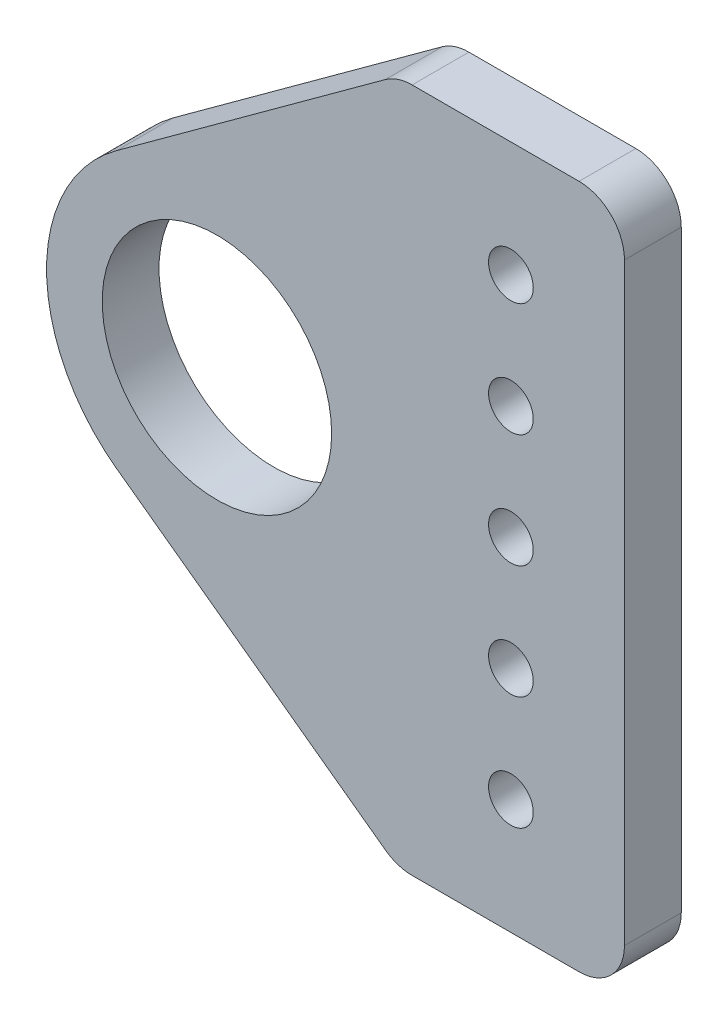
SolidWorks part; units mm, degrees
ref_plane "Front Plane" through (0, 0, 0) normal (0, 0, 1) x (1, 0, 0)
ref_plane "Top Plane" through (0, 0, 0) normal (0, 1, 0) x (1, 0, 0)
ref_plane "Right Plane" through (0, 0, 0) normal (1, 0, 0) x (0, 0, -1)
sketch "Sketch1" plane through (0, 0, 0) normal (0, 0, 1) x (1, 0, 0)
  line L0 (7.62, 952.6788) -> (-11.045, 952.6788)
  line L1 (12.7, 1181.1) -> (12.7, 876.3) construction
  line L2 (-12.7, 1181.1) -> (-12.7, 876.3) construction
  line L3 (-14.0374, 951.7039) -> (-44.0944, 929.7942)
  line L4 (2.5, 914.4) -> (50002.5, 914.4) construction
  line L5 (-14.0374, 877.0961) -> (-44.0944, 899.0058)
  line L6 (7.62, 876.1212) -> (-11.045, 876.1212)
  line L7 (12.7, 881.2012) -> (12.7, 947.5988)
  arc A0 (0.127, 911.9032) -> (0.127, 916.8968) centre (0, 914.4) ccw construction
  arc A1 (-44.0944, 929.7942) -> (-44.0944, 899.0058) centre (-32.8729, 914.4) ccw
  circle A2 centre (-32.8729, 914.4) radius 12.827
  circle A3 centre (0, 939.8) radius 2.5
  circle A4 centre (0, 927.1) radius 2.5
  circle A5 centre (0, 914.4) radius 2.5
  circle A6 centre (0, 901.7) radius 2.5
  circle A7 centre (0, 889) radius 2.5
  arc A8 (-11.045, 952.6788) -> (-14.0374, 951.7039) centre (-11.045, 947.5988) ccw
  arc A9 (-14.0374, 877.0961) -> (-11.045, 876.1212) centre (-11.045, 881.2012) ccw
  arc A10 (7.62, 876.1212) -> (12.7, 881.2012) centre (7.62, 881.2012) ccw
  arc A11 (7.62, 952.6788) -> (12.7, 947.5988) centre (7.62, 947.5988) cw
  point P12 (2.5, 914.4)
  point P31 (-12.7, 952.6788)
  point P34 (-12.7, 876.1212)
  point P37 (12.7, 876.1212)
  point P40 (12.7, 952.6788)
  dimension "D1" = 19.05
  dimension "D3" = 5.08
  dimension "D2" = 5
extrude "Boss-Extrude1" add sketch "Sketch1" along normal blind 6.35
